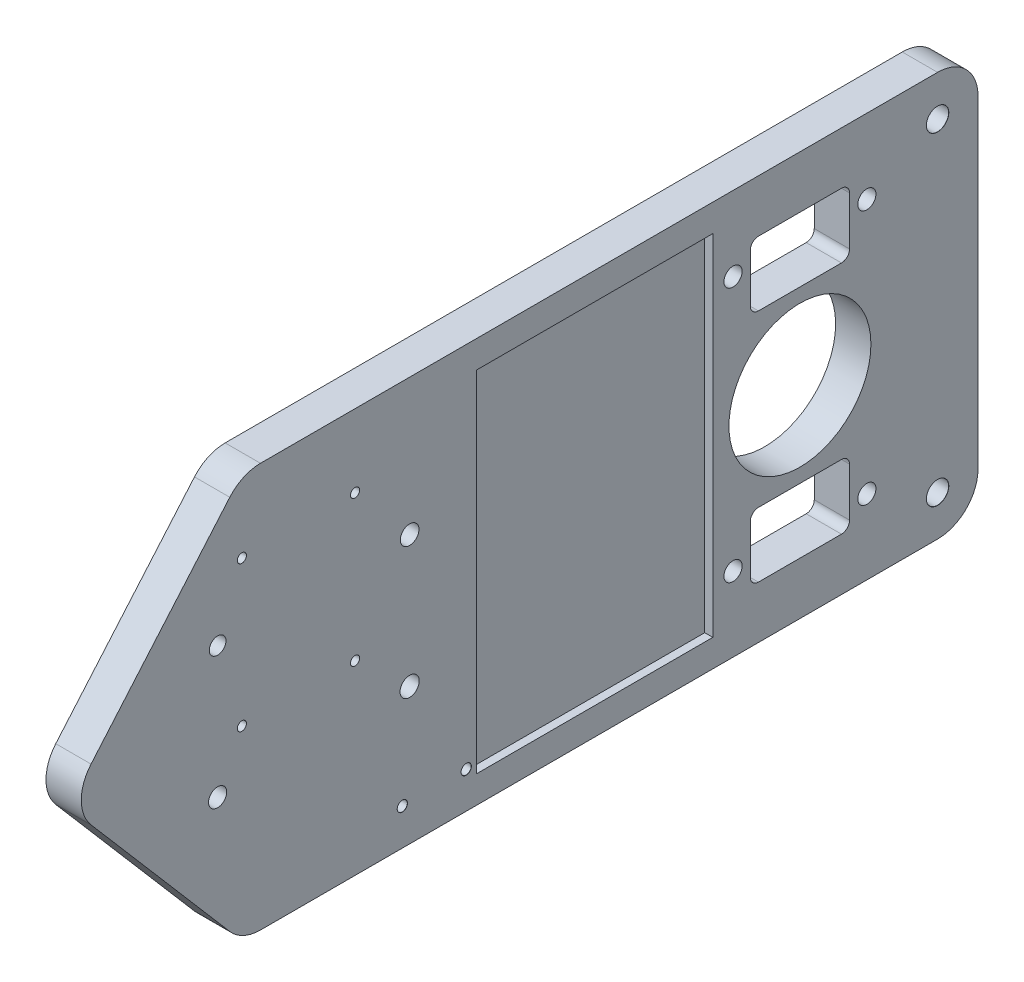
SolidWorks part; units mm, degrees
other "Chassis"
other "Bearing Plate"
other "IMU"
other "Bearing Plate 2"
material "Nylon 101"
ref_plane "Front Plane" through (0, 0, 0) normal (1, 0, 0) x (0, 1, 0)
ref_plane "Top Plane" through (0, 0, 0) normal (0, 0, 1) x (0, 1, 0)
ref_plane "Right Plane" through (0, 0, 0) normal (0, 1, 0) x (-1, 0, 0)
sketch "Sketch1" plane through (0, 0, 0) normal (1, 0, 0) x (0, 1, 0)
  line L0 (-50, 138.05) -> (-50, -44.05)
  line L1 (-50, -44.05) -> (50, -44.05)
  line L2 (50, -44.05) -> (50, 138.05)
  line L3 (50, 138.05) -> (0, 180.95)
  line L4 (0, 180.95) -> (-50, 138.05)
  line L5 (0, 180.95) -> (0, 0) construction
  line L6 (-50, 138.05) -> (0, 138.05) construction
  line L7 (0, 138.05) -> (50, 138.05) construction
  line L8 (-448.1018, -246.5596) -> (346.2414, -246.5596) construction
  line L9 (0, 77.55) -> (0, 138.05) construction
  line L10 (-40.75, 77.55) -> (40.75, 77.55)
  line L11 (-40.75, 77.55) -> (-40.75, 24.05)
  line L12 (-40.75, 24.05) -> (40.75, 24.05)
  line L13 (40.75, 77.55) -> (40.75, 24.05)
  line L14 (-40, -34.05) -> (40, -34.05) construction
  line L15 (-40, -24.05) -> (40, -24.05)
  line L16 (-40, -44.05) -> (40, -44.05)
  line L17 (0, -34.05) -> (0, 0) construction
  line L18 (-41, 98.35) -> (-41, 82.55) construction
  line L19 (-38.525, 100.825) -> (-38.525, 80.075)
  line L20 (-38.525, 100.825) -> (-54.025, 100.825)
  line L21 (-54.025, 100.825) -> (-54.025, 80.075)
  line L22 (-38.525, 80.075) -> (-54.025, 80.075)
  line L23 (-41, 90.45) -> (-54.025, 90.45) construction
  line L24 (-41, 100.825) -> (-41, 98.35) construction
  line L25 (-41, 98.35) -> (-38.525, 98.35) construction
  line L26 (-38.525, 80.075) -> (-38.525, 77.55) construction
  line L27 (-7, 124.05) -> (-4, 124.05) construction
  line L32 (-12.5, 149.05) -> (12.5, 149.05)
  line L33 (-12.5, 149.05) -> (-12.5, 89.05)
  line L34 (-12.5, 89.05) -> (12.5, 89.05)
  line L35 (12.5, 149.05) -> (12.5, 89.05)
  line L36 (-7, 140.55) -> (35, 140.55)
  line L37 (-7, 140.55) -> (-7, 107.55)
  line L38 (-7, 107.55) -> (35, 107.55)
  line L39 (35, 140.55) -> (35, 107.55)
  line L40 (-4, 138.05) -> (32, 138.05) construction
  line L41 (-4, 138.05) -> (-4, 110.05) construction
  line L42 (-4, 110.05) -> (32, 110.05) construction
  line L43 (32, 138.05) -> (32, 110.05) construction
  line L44 (14, 138.05) -> (14, 140.55) construction
  circle A0 centre (0, 0) radius 6.35 construction
  circle A1 centre (0, 0) radius 17.4625 construction
  circle A2 centre (0, 0) radius 19.05 construction
  circle A3 centre (0, 0) radius 17.5641
  arc A4 (-40, -24.05) -> (-40, -44.05) centre (-40, -34.05) ccw
  arc A5 (40, -44.05) -> (40, -24.05) centre (40, -34.05) ccw
  circle A6 centre (-41, 98.35) radius 1.5
  circle A7 centre (-41, 82.55) radius 1.5
  point P22 (0, -34.05)
  point P61 (28.7552, 136.6008)
  point P62 (34.4141, 107.5176)
  point P63 (-8.3811, 109.6248)
  point P64 (-80.9611, 47.9157)
  point P65 (-54.025, 114.4156)
  point P66 (0, 0)
  point P67 (50, 130.4291)
  point P68 (50, 133.9364)
  point P69 (0, 177.9226)
  point P70 (50, 126.2409)
  point P71 (0, 175.1221)
  point P72 (50, 118.1709)
  point P73 (-50, 116.733)
  point P74 (0, 178.693)
  point P75 (0, 171.4908)
  point P76 (0, 206.381)
  point P77 (-50, 104.85)
  point P78 (0, 203.0559)
  point P79 (-50, 115.4662)
  point P80 (50, 117.508)
  point P81 (32.634, 97.55)
  point P82 (14, 144.7601)
  point P83 (0, 89.05)
  point P84 (12.5, 86.1313)
  point P85 (12.5, 65.2674)
  point P86 (-12.5, 139.0149)
  dimension "D5" = 12.7
  dimension "D6" = 34.925
  dimension "D8" = 38.1
  dimension "D9" = 0.1016
  dimension "D10" = 35.1282
  dimension "D14" = 10
  dimension "D3" = 5
  dimension "D15" = 5
  dimension "D18" = 3
  dimension "D20" = 7.5
  dimension "D25" = 36
  dimension "D30" = 8.5
  dimension "D27" = 30
  dimension "D28" = 15
  dimension "D29" = 5
  dimension "D4" = 100
  dimension "D7" = 246.5596
  dimension "D11" = 81.5
  dimension "D12" = 53.5
  dimension "D13" = 25
  dimension "D16" = 15.5
  dimension "D17" = 20.75
  dimension "D19" = 15.8
  dimension "D21" = 60
  dimension "D22" = 225
  dimension "D23" = 42
  dimension "D24" = 33
  dimension "D26" = 28
extrude "Boss-Extrude1" add sketch "Sketch1" along normal mid plane 8.7312
sketch "Sketch2" plane through (4.3656, 0, 0) normal (1, 0, 0) x (0, 1, 0)
  line L0 (-39.05, 0) -> (-19.05, 0) construction
  line L1 (-39.05, 21.55) -> (39.05, 21.55)
  line L2 (-39.05, 21.55) -> (-39.05, -21.55)
  line L3 (-39.05, -21.55) -> (39.05, -21.55)
  line L4 (39.05, 21.55) -> (39.05, -21.55)
  line L5 (19.05, 0) -> (39.05, 0) construction
  line L6 (-31.55, 16.55) -> (31.55, 16.55) construction
  line L7 (31.55, 16.55) -> (31.55, -16.55) construction
  line L8 (31.55, -16.55) -> (-31.55, -16.55) construction
  line L9 (-31.55, -16.55) -> (-31.55, 16.55) construction
  line L10 (0, 16.55) -> (0, 21.55) construction
  line L11 (31.55, 0) -> (39.05, 0) construction
  line L12 (-31.55, 24.05) -> (-31.55, 16.55) construction
  line L13 (-31.55, 16.55) -> (-39.05, 16.55) construction
  line L14 (-40.75, 24.05) -> (40.75, 24.05) construction
  circle A1 centre (0, 0) radius 19.05 construction
  circle A2 centre (-31.55, 16.55) radius 2 construction
  circle A3 centre (-31.55, -16.55) radius 2 construction
  circle A4 centre (31.55, 16.55) radius 2 construction
  circle A5 centre (31.55, -16.55) radius 2 construction
  point P21 (-39.05, -24.05)
  point P25 (-39.05, -21.9111)
  point P26 (0, 21.9111)
  point P27 (0, 0)
  point P28 (-31.55, 24.05)
  point P31 (39.05, -20.8519)
  dimension "D1" = 20
  dimension "D3" = 4
  dimension "D2" = 7.5
  dimension "D4" = 2.5
extrude "Boss-Extrude2" add sketch "Sketch2" along normal blind 8.7312 separate body
sketch "Sketch3" plane through (13.0969, 0, 0) normal (1, 0, 0) x (0, 1, 0)
  circle A0 centre (0, 0) radius 17.5641 construction
  circle A1 centre (0, 0) radius 17.5641
hole_wizard "M4 Clearance Hole2" positions "Sketch22" profile "Sketch23" hole size "M4" standard "ANSI Metric" end condition through all
sketch "Sketch22" plane through (13.0969, 0, 0) normal (1, 0, 0) x (0, 1, 0)
  point P0 (-31.55, 16.55)
  point P3 (-31.55, -16.55)
  point P6 (31.55, -16.55)
  point P9 (31.55, 16.55)
sketch "Sketch23" plane through (13.0969, -31.55, 16.55) normal (0, 1, 0) x (0, 0, -1)
  line L0 (0, 0) -> (0, 17.4625)
  line L1 (0, 17.4625) -> (2.25, 17.4625)
  line L2 (2.25, 17.4625) -> (2.25, 0.025)
  line L3 (2.25, 0.025) -> (2.275, 0)
  line L5 (2.275, 0) -> (0, 0)
  line L6 (-2.25, 0.025) -> (-2.275, 0) construction
  line L11 (0, -6.35) -> (0, 107.95) construction
  dimension "Thru Hole Dia." = 4.5
  dimension "Thru Hole Depth" = 17.4625
  dimension "Near C'Sink Dia." = 4.55
  dimension "Near C'Sink Angle" = 90
sketch "Sketch24" plane through (-4.3656, 0, 0) normal (-1, 0, 0) x (0, -1, 0)
  line L0 (39.05, 21.55) -> (39.05, -21.55) construction
  line L1 (39.05, -21.55) -> (-39.05, -21.55) construction
  line L2 (-39.05, 21.55) -> (-39.05, -21.55) construction
  line L3 (39.05, 21.55) -> (-39.05, 21.55) construction
  line L4 (39.05, 21.55) -> (39.05, -21.55)
  line L5 (39.05, -21.55) -> (-39.05, -21.55)
  line L6 (-39.05, 21.55) -> (-39.05, -21.55)
  line L7 (39.05, 21.55) -> (-39.05, 21.55)
extrude "Boss-Extrude3" add sketch "Sketch24" along normal blind 8.7312 separate body
hole_wizard "Tap Drill for M4x0.7 Tap1" positions "Sketch25" profile "Sketch27" hole size "M4x0.7" standard "ANSI Metric"
sketch "Sketch25" plane through (-13.0969, 0, 0) normal (-1, 0, 0) x (0, -1, 0)
  point P0 (-31.55, 16.55)
  point P2 (-31.55, -16.55)
  point P4 (31.55, -16.55)
  point P6 (31.55, 16.55)
sketch "Sketch27" plane through (-13.0969, 31.55, 16.55) normal (0, 1, 0) x (0, 0, 1)
  line L0 (0, 0) -> (0, 9.7227)
  line L1 (0, 9.7227) -> (1.65, 8.7312)
  line L2 (1.65, 8.7312) -> (1.65, 0.025)
  line L3 (1.65, 0.025) -> (1.675, 0)
  line L5 (1.675, 0) -> (0, 0)
  line L6 (-1.65, 0.025) -> (-1.675, 0) construction
  line L10 (0, 9.7227) -> (-1.65, 8.7312) construction
  line L11 (0, -6.35) -> (0, 107.95) construction
  dimension "Hole Dia." = 3.3
  dimension "Hole Depth" = 8.7312
  dimension "Near C'Sink Dia." = 3.35
  dimension "Near C'Sink Angle" = 90
  dimension "Drill Angle" = 118
hole_wizard "Tap Drill for M3x0.5 Tap1" positions "Sketch9" profile "Sketch10" hole size "M3x0.5" standard "ANSI Metric" end condition through all
sketch "Sketch9" plane through (4.3656, 0, 0) normal (1, 0, 0) x (0, 1, 0)
  point P0 (-41, 98.35)
  point P3 (-41, 82.55)
sketch "Sketch10" plane through (4.3656, -41, 98.35) normal (0, 1, 0) x (0, 0, -1)
  line L0 (0, 0) -> (0, 17.4625)
  line L1 (0, 17.4625) -> (1.25, 17.4625)
  line L2 (1.25, 17.4625) -> (1.25, 0.025)
  line L3 (1.25, 0.025) -> (1.275, 0)
  line L5 (1.275, 0) -> (0, 0)
  line L6 (-1.25, 0.025) -> (-1.275, 0) construction
  line L11 (0, -6.35) -> (0, 107.95) construction
  dimension "Thru Hole Dia." = 2.5
  dimension "Thru Hole Depth" = 17.4625
  dimension "Near C'Sink Dia." = 2.55
  dimension "Near C'Sink Angle" = 90
extrude "Cut-Extrude3" cut sketch "Sketch3" against normal through all
hole_wizard "M5 Clearance Hole1" positions "Sketch13" profile "Sketch12" hole size "M5" standard "ANSI Metric" end condition through all
sketch "Sketch13" plane through (4.3656, 0, 0) normal (1, 0, 0) x (0, 1, 0)
  point P0 (-40, -34.05)
  point P3 (40, -34.05)
sketch "Sketch12" plane through (4.3656, -40, -34.05) normal (0, 1, 0) x (0, 0, -1)
  line L0 (0, 0) -> (0, 17.4625)
  line L1 (0, 17.4625) -> (2.75, 17.4625)
  line L2 (2.75, 17.4625) -> (2.75, 0.025)
  line L3 (2.75, 0.025) -> (2.775, 0)
  line L5 (2.775, 0) -> (0, 0)
  line L6 (-2.75, 0.025) -> (-2.775, 0) construction
  line L11 (0, -6.35) -> (0, 107.95) construction
  dimension "Thru Hole Dia." = 5.5
  dimension "Thru Hole Depth" = 17.4625
  dimension "Near C'Sink Dia." = 5.55
  dimension "Near C'Sink Angle" = 90
sketch "Sketch14" plane through (4.3656, 0, 0) normal (1, 0, 0) x (0, 1, 0)
  line L8 (43.25, 21.55) -> (43.25, 80.05)
  line L9 (-43.25, 21.55) -> (43.25, 21.55)
  line L10 (-43.25, 80.05) -> (-43.25, 21.55)
  line L11 (43.25, 80.05) -> (-43.25, 80.05)
  line L12 (43.25, 21.55) -> (43.25, 80.05)
  line L13 (-43.25, 21.55) -> (43.25, 21.55)
  line L14 (-43.25, 80.05) -> (-43.25, 21.55)
  line L15 (43.25, 80.05) -> (-43.25, 80.05)
  dimension "D1" = 2.5
extrude "Cut-Extrude4" cut sketch "Sketch14" against normal blind 2
fillet "Fillet4" radius 10 5 edges at (0, 50, -44.05) (0, -50, -44.05) (0, 50, 138.05) (0, 0, 180.95) (0, -50, 138.05)
fillet "Fillet5" radius 5 4 edges at (-8.7312, -39.05, 21.55) (-8.7312, -39.05, -21.55) (-8.7312, 39.05, -21.55) (-8.7312, 39.05, 21.55)
fillet "Fillet6" radius 5 4 edges at (8.7312, -39.05, 21.55) (8.7312, 39.05, -21.55) (8.7312, -39.05, -21.55) (8.7312, 39.05, 21.55)
sketch "Sketch28" plane through (4.3656, 0, 0) normal (1, 0, 0) x (0, 1, 0)
  line L0 (-38.525, 100.825) -> (-54.025, 100.825) construction
  line L1 (-38.525, 100.825) -> (-54.025, 100.825)
  line L2 (-54.025, 100.825) -> (-54.025, 80.075) construction
  line L3 (-54.025, 100.825) -> (-54.025, 80.075)
  line L4 (-38.525, 100.825) -> (-38.525, 80.075) construction
  line L5 (-38.525, 100.825) -> (-38.525, 80.075)
  line L6 (-38.525, 80.075) -> (-54.025, 80.075) construction
  line L7 (-38.525, 80.075) -> (-54.025, 80.075)
  circle A0 centre (-41, 82.55) radius 1.5 construction
  circle A1 centre (-41, 82.55) radius 1.5
  circle A2 centre (-41, 98.35) radius 1.5 construction
  circle A3 centre (-41, 98.35) radius 1.5
extrude "Boss-Extrude4" add sketch "Sketch28" along normal blind 2.5 separate body
fillet "Fillet7" radius 1 4 edges at (5.6156, -38.525, 100.825) (5.6156, -38.525, 80.075) (5.6156, -54.025, 80.075) (5.6156, -54.025, 100.825)
sketch "Sketch29" plane through (4.3656, 0, 0) normal (-1, 0, 0) x (0, -1, 0)
  line L0 (52.025, 100.825) -> (52.025, 80.075) construction
  line L1 (52.025, 90.45) -> (54.025, 90.45) construction
  line L3 (53.025, 80.075) -> (39.525, 80.075) construction
  line L4 (54.025, 99.825) -> (54.025, 81.075) construction
  line L6 (52.025, 80.2) -> (52.025, 80.075) construction
  line L8 (52.025, 100.825) -> (52.025, 100.7) construction
  circle A6 centre (52.025, 99.2) radius 1.5
  circle A7 centre (52.025, 95.7) radius 1.5
  circle A8 centre (52.025, 92.2) radius 1.5
  circle A9 centre (52.025, 88.7) radius 1.5
  circle A10 centre (52.025, 85.2) radius 1.5
  circle A11 centre (52.025, 81.7) radius 1.5
  dimension "D3" = 6
  dimension "D2" = 3
  dimension "D4" = 0.5
  dimension "D1" = 2
extrude "Boss-Extrude5" add sketch "Sketch29" along normal blind 1.5
fillet "Fillet8" radius 0.5 6 edges at (2.8656, -52.025, 83.2) (2.8656, -52.025, 86.7) (2.8656, -52.025, 90.2) (2.8656, -52.025, 93.7) (2.8656, -52.025, 97.2) (2.8656, -52.025, 100.7)
hole_wizard "Tap Drill for #4-40 Tap1" positions "Sketch33" profile "Sketch34" hole size "#4-40" standard "ANSI Inch" end condition through all
sketch "Sketch33" plane through (4.3656, 0, 0) normal (1, 0, 0) x (0, 1, 0)
  point P0 (-4, 138.05)
  point P3 (-4, 110.05)
  point P6 (32, 110.05)
  point P9 (32, 138.05)
sketch "Sketch34" plane through (4.3656, -4, 138.05) normal (0, 1, 0) x (0, 0, -1)
  line L0 (0, 0) -> (0, 17.4625)
  line L1 (0, 17.4625) -> (1.1303, 17.4625)
  line L2 (1.1303, 17.4625) -> (1.1303, 0)
  line L5 (1.1303, 0) -> (0, 0)
  line L11 (0, -6.35) -> (0, 107.95) construction
  dimension "Thru Hole Dia." = 2.2606
  dimension "Thru Hole Depth" = 17.4625
sketch "Sketch35" plane through (4.3656, 0, 0) normal (1, 0, 0) x (0, 1, 0)
  line L0 (-16.25, 144.05) -> (16.25, 144.05) construction
  line L1 (0, 180.95) -> (0, 0) construction
  line L2 (-16.25, 144.05) -> (-16.25, 96.55) construction
  line L3 (16.25, 144.05) -> (16.25, 96.55) construction
  line L4 (-16.25, 96.55) -> (16.25, 96.55) construction
  line L5 (-12.5, 149.05) -> (12.5, 149.05) construction
  line L6 (-12.5, 89.05) -> (12.5, 89.05) construction
  circle A0 centre (-16.25, 144.05) radius 2.25
  circle A1 centre (16.25, 144.05) radius 2.065
  circle A2 centre (-16.25, 96.55) radius 2.3737
  circle A3 centre (16.25, 96.55) radius 2.3096
  point P8 (-16.25, 86.7638)
  point P9 (0, 144.05)
  point P12 (16.25, 134.038)
  dimension "D1" = 4.5
  dimension "D2" = 32.5
  dimension "D3" = 5
  dimension "D4" = 7.5
extrude "Cut-Extrude5" cut sketch "Sketch35" against normal through all
sketch "Sketch36" plane through (13.0969, 0, 0) normal (1, 0, 0) x (0, 1, 0)
  line L0 (-39.05, 16.55) -> (-39.05, -16.55) construction
  line L1 (-37.05, 12.275) -> (-21.05, 12.275)
  line L2 (-37.05, 12.275) -> (-37.05, -12.275)
  line L3 (-37.05, -12.275) -> (-21.05, -12.275)
  line L4 (-21.05, 12.275) -> (-21.05, -12.275)
  line L5 (0, 0) -> (0, 21.55) construction
  line L6 (34.05, 21.55) -> (-34.05, 21.55) construction
  line L7 (21.05, 12.275) -> (21.05, -12.275)
  line L8 (37.05, -12.275) -> (21.05, -12.275)
  line L9 (37.05, 12.275) -> (37.05, -12.275)
  line L10 (37.05, 12.275) -> (21.05, 12.275)
  circle A1 centre (0, 0) radius 19.05 construction
  circle A3 centre (-31.55, 16.55) radius 2.275 construction
  circle A5 centre (-31.55, -16.55) radius 2.275 construction
  dimension "D1" = 2
  dimension "D2" = 2
  dimension "D3" = 2
  dimension "D4" = 2
extrude "Cut-Extrude6" cut sketch "Sketch36" against normal through all
fillet "Fillet9" radius 2 8 edges at (8.7312, -37.05, 12.275) (8.7312, 21.05, -12.275) (8.7312, 37.05, -12.275) (8.7312, 37.05, 12.275) (8.7312, 21.05, 12.275) (8.7312, -21.05, -12.275) (8.7312, -37.05, -12.275) (8.7312, -21.05, 12.275)
fillet "Fillet10" radius 2 8 edges at (-8.7313, -21.05, 12.275) (-8.7313, -21.05, -12.275) (-8.7313, -37.05, -12.275) (-8.7313, -37.05, 12.275) (-8.7313, 37.05, -12.275) (-8.7313, 21.05, -12.275) (-8.7313, 21.05, 12.275) (-8.7313, 37.05, 12.275)
delete or keep bodies "Body-Delete/Keep 1" type keep bodies bodies 138
fillet "Fillet11" radius 2 8 edges at (0, 37.05, -12.275) (0, 21.05, -12.275) (0, 37.05, 12.275) (0, 21.05, 12.275) (0, -21.05, 12.275) (0, -21.05, -12.275) (0, -37.05, -12.275) (0, -37.05, 12.275)
